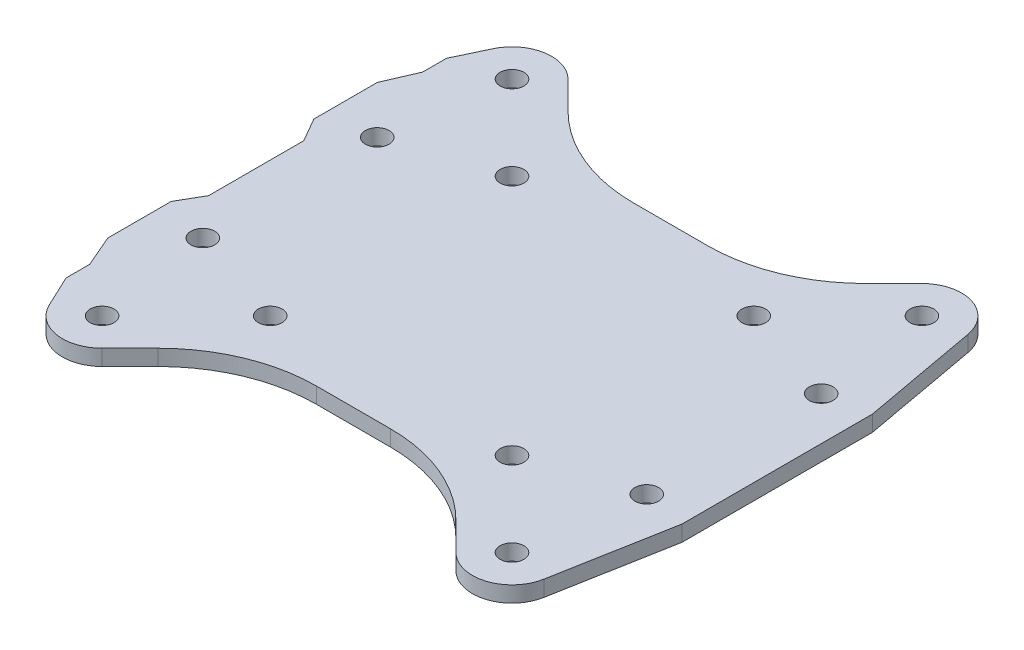
SolidWorks part; units mm, degrees
ref_plane "Front Plane" through (0, 0, 0) normal (0, 0, 1) x (1, 0, 0)
ref_plane "Top Plane" through (0, 0, 0) normal (0, 1, 0) x (1, 0, 0)
ref_plane "Right Plane" through (0, 0, 0) normal (1, 0, 0) x (0, 0, -1)
sketch "Sketch1" plane through (0, 0, 0) normal (0, 1, 0) x (1, 0, 0)
  line L0 (-95.7448, 37.8624) -> (-97.1796, 23.5084)
  line L1 (-97.1796, 23.5084) -> (-97.1796, -0.4916)
  line L2 (-97.1796, -0.4916) -> (-95.7448, -14.8455)
  line L3 (-97.1796, -0.4916) -> (-97.1796, -12.4916)
  line L4 (-46.1262, 37.3663) -> (-42.5919, 40.9006)
  line L5 (-69.5577, 31.5084) -> (-60.2683, 31.5084)
  line L6 (-83.6998, 37.3663) -> (-87.2341, 40.9006)
  line L7 (-97.1796, -12.4916) -> (-95.2892, -16.4868)
  line L8 (-83.6998, -14.3494) -> (-87.2341, -17.8837)
  line L9 (-60.2683, -8.4916) -> (-69.5577, -8.4916)
  line L10 (-46.1262, -14.3494) -> (-42.5919, -17.8837)
  line L11 (-97.1796, 23.5084) -> (-97.1796, 35.5084)
  line L12 (-97.1796, 35.5084) -> (-95.2892, 39.5036)
  line L13 (-97.1796, 5.5084) -> (-98.9096, 2.5084)
  line L14 (-98.9096, 2.5084) -> (-98.9096, -5.4916)
  line L15 (-98.9096, -5.4916) -> (-97.1796, -9.4916)
  line L16 (-97.1796, 17.5084) -> (-98.9096, 20.5084)
  line L17 (-98.9096, 20.5084) -> (-98.9096, 28.5084)
  line L18 (-98.9096, 28.5084) -> (-97.1796, 32.5084)
  line L22 (-34.1375, -15.2449) -> (-31.4479, -0.4916)
  line L23 (-34.1375, 38.2618) -> (-31.4479, 23.5084)
  line L24 (-31.4479, 23.5084) -> (-31.4479, -0.4916)
  arc A4 (-34.1375, 38.2618) -> (-42.5919, 40.9006) centre (-39.0564, 37.365) ccw
  arc A5 (-60.2683, 31.5084) -> (-46.1262, 37.3663) centre (-60.2683, 51.5084) ccw
  arc A6 (-83.6998, 37.3663) -> (-69.5577, 31.5084) centre (-69.5577, 51.5084) ccw
  arc A7 (-87.2341, 40.9006) -> (-95.7448, 37.8624) centre (-90.7696, 37.365) ccw
  arc A10 (-95.7448, -14.8455) -> (-87.2341, -17.8837) centre (-90.7696, -14.3482) ccw
  arc A11 (-69.5577, -8.4916) -> (-83.6998, -14.3494) centre (-69.5577, -28.4916) ccw
  arc A12 (-46.1262, -14.3494) -> (-60.2683, -8.4916) centre (-60.2683, -28.4916) ccw
  arc A13 (-42.5919, -17.8837) -> (-34.1375, -15.2449) centre (-39.0564, -14.3482) ccw
  circle A18 centre (-90.7696, 37.365) radius 1.5
  circle A19 centre (-92.913, 22.5084) radius 1.5
  circle A20 centre (-92.913, 0.5084) radius 1.5
  circle A21 centre (-36.913, 0.5084) radius 1.5
  circle A22 centre (-36.913, 22.5084) radius 1.5
  circle A23 centre (-49.663, 26.7584) radius 1.5
  circle A24 centre (-80.163, 26.7584) radius 1.5
  circle A25 centre (-80.163, -3.7416) radius 1.5
  circle A26 centre (-49.663, -3.7416) radius 1.5
  circle A29 centre (-90.7696, -14.3482) radius 1.5
  circle A38 centre (-39.0564, 37.365) radius 1.5
  circle A39 centre (-39.0564, -14.3482) radius 1.5
  dimension "D1" = 14.7533
  dimension "D2" = 14.7533
  dimension "D3" = 24
  dimension "D4" = 24
  dimension "D5" = 14.3539
  dimension "D6" = 14.3539
  dimension "D7" = 12
  dimension "D8" = 12
  dimension "D9" = 1.73
  dimension "D10" = 1.73
  dimension "D11" = 6
  dimension "D12" = 2
  dimension "D13" = 2
  dimension "D14" = 6
  dimension "D15" = 4
  dimension "D16" = 3
  dimension "D17" = 3
  dimension "D18" = 4
extrude "Boss-Extrude1" add sketch "Sketch1" along normal blind 2 contours L10 A13 L22 L24 L23 A4 L4 A5 L5 A6 L6 A7 L0 L1 L2 A10 L8 A11 L9 A12 A39 A38 A29 A26 A25 A24 A23 A22 A21 A20 A19 A18 | A10 L2 L3 L7 | A7 L12 L11 L0 | L18 L17 L16 L1 L11 | L14 L15 L3 L1 L13
sketch "Sketch2" plane through (0, 0, 0) normal (0, -1, 0) x (1, 0, 0)
  line L0 (-30.913, -23.261) -> (-32.413, -24.761) construction
  line L1 (-30.913, -23.261) -> (-32.413, -24.761)
  line L2 (-32.413, 5.7441) -> (-30.913, 7.2441) construction
  line L3 (-32.413, 1.7441) -> (-32.413, 5.7441) construction
  line L4 (-32.413, -24.761) -> (-32.413, -28.761) construction
  line L5 (-32.413, 5.7441) -> (-30.913, 7.2441)
  line L6 (-32.413, 1.7441) -> (-32.413, 5.7441)
  line L7 (-32.413, -24.761) -> (-32.413, -28.761)
  line L20 (-97.1796, 9.4916) -> (-98.9096, 5.4916)
  line L21 (-98.9096, 5.4916) -> (-98.9096, -2.5084)
  line L22 (-98.9096, -2.5084) -> (-97.1796, -5.5084)
  line L23 (-97.1796, -5.5084) -> (-97.1796, -17.5084)
  line L24 (-97.1796, -17.5084) -> (-98.9096, -20.5084)
  line L25 (-98.9096, -20.5084) -> (-98.9096, -28.5084)
  line L26 (-98.9096, -28.5084) -> (-97.1796, -32.5084)
  line L27 (-97.1796, -32.5084) -> (-97.1796, -35.5084)
  line L28 (-97.1796, -35.5084) -> (-95.2892, -39.5036)
  line L29 (-87.2341, -40.9006) -> (-83.6998, -37.3663)
  line L30 (-69.5577, -31.5084) -> (-60.2683, -31.5084)
  line L31 (-46.1262, -37.3663) -> (-42.5919, -40.9006)
  line L32 (-34.1375, -38.2618) -> (-31.4479, -23.5084)
  line L33 (-31.4479, -23.5084) -> (-31.4479, 0.4916)
  line L34 (-31.4479, 0.4916) -> (-34.1375, 15.2449)
  line L35 (-42.5919, 17.8837) -> (-46.1262, 14.3494)
  line L36 (-60.2683, 8.4916) -> (-69.5577, 8.4916)
  line L37 (-83.6998, 14.3494) -> (-87.2341, 17.8837)
  line L38 (-95.2892, 16.4868) -> (-97.1796, 12.4916)
  line L39 (-97.1796, 12.4916) -> (-97.1796, 9.4916)
  line L40 (-97.1796, 9.4916) -> (-98.9096, 5.4916)
  line L41 (-98.9096, 5.4916) -> (-98.9096, -2.5084)
  line L42 (-98.9096, -2.5084) -> (-97.1796, -5.5084)
  line L43 (-97.1796, -5.5084) -> (-97.1796, -17.5084)
  line L44 (-97.1796, -17.5084) -> (-98.9096, -20.5084)
  line L45 (-98.9096, -20.5084) -> (-98.9096, -28.5084)
  line L46 (-98.9096, -28.5084) -> (-97.1796, -32.5084)
  line L47 (-97.1796, -32.5084) -> (-97.1796, -35.5084)
  line L48 (-97.1796, -35.5084) -> (-95.2892, -39.5036)
  line L49 (-87.2341, -40.9006) -> (-83.6998, -37.3663)
  line L50 (-69.5577, -31.5084) -> (-60.2683, -31.5084)
  line L51 (-46.1262, -37.3663) -> (-42.5919, -40.9006)
  line L52 (-34.1375, -38.2618) -> (-31.4479, -23.5084)
  line L53 (-31.4479, -23.5084) -> (-31.4479, 0.4916)
  line L54 (-31.4479, 0.4916) -> (-34.1375, 15.2449)
  line L55 (-42.5919, 17.8837) -> (-46.1262, 14.3494)
  line L56 (-60.2683, 8.4916) -> (-69.5577, 8.4916)
  line L57 (-83.6998, 14.3494) -> (-87.2341, 17.8837)
  line L58 (-95.2892, 16.4868) -> (-97.1796, 12.4916)
  line L59 (-97.1796, 12.4916) -> (-97.1796, 9.4916)
  arc A8 (-95.2892, -39.5036) -> (-87.2341, -40.9006) centre (-90.7696, -37.365) ccw
  arc A9 (-69.5577, -31.5084) -> (-83.6998, -37.3663) centre (-69.5577, -51.5084) ccw
  arc A10 (-46.1262, -37.3663) -> (-60.2683, -31.5084) centre (-60.2683, -51.5084) ccw
  arc A11 (-42.5919, -40.9006) -> (-34.1375, -38.2618) centre (-39.0564, -37.365) ccw
  arc A12 (-34.1375, 15.2449) -> (-42.5919, 17.8837) centre (-39.0564, 14.3482) ccw
  arc A13 (-60.2683, 8.4916) -> (-46.1262, 14.3494) centre (-60.2683, 28.4916) ccw
  arc A14 (-83.6998, 14.3494) -> (-69.5577, 8.4916) centre (-69.5577, 28.4916) ccw
  arc A15 (-87.2341, 17.8837) -> (-95.2892, 16.4868) centre (-90.7696, 14.3482) ccw
  arc A16 (-95.2892, -39.5036) -> (-87.2341, -40.9006) centre (-90.7696, -37.365) ccw
  arc A17 (-69.5577, -31.5084) -> (-83.6998, -37.3663) centre (-69.5577, -51.5084) ccw
  arc A18 (-46.1262, -37.3663) -> (-60.2683, -31.5084) centre (-60.2683, -51.5084) ccw
  arc A19 (-42.5919, -40.9006) -> (-34.1375, -38.2618) centre (-39.0564, -37.365) ccw
  arc A20 (-34.1375, 15.2449) -> (-42.5919, 17.8837) centre (-39.0564, 14.3482) ccw
  arc A21 (-60.2683, 8.4916) -> (-46.1262, 14.3494) centre (-60.2683, 28.4916) ccw
  arc A22 (-83.6998, 14.3494) -> (-69.5577, 8.4916) centre (-69.5577, 28.4916) ccw
  arc A23 (-87.2341, 17.8837) -> (-95.2892, 16.4868) centre (-90.7696, 14.3482) ccw
  dimension "D1" = 0
